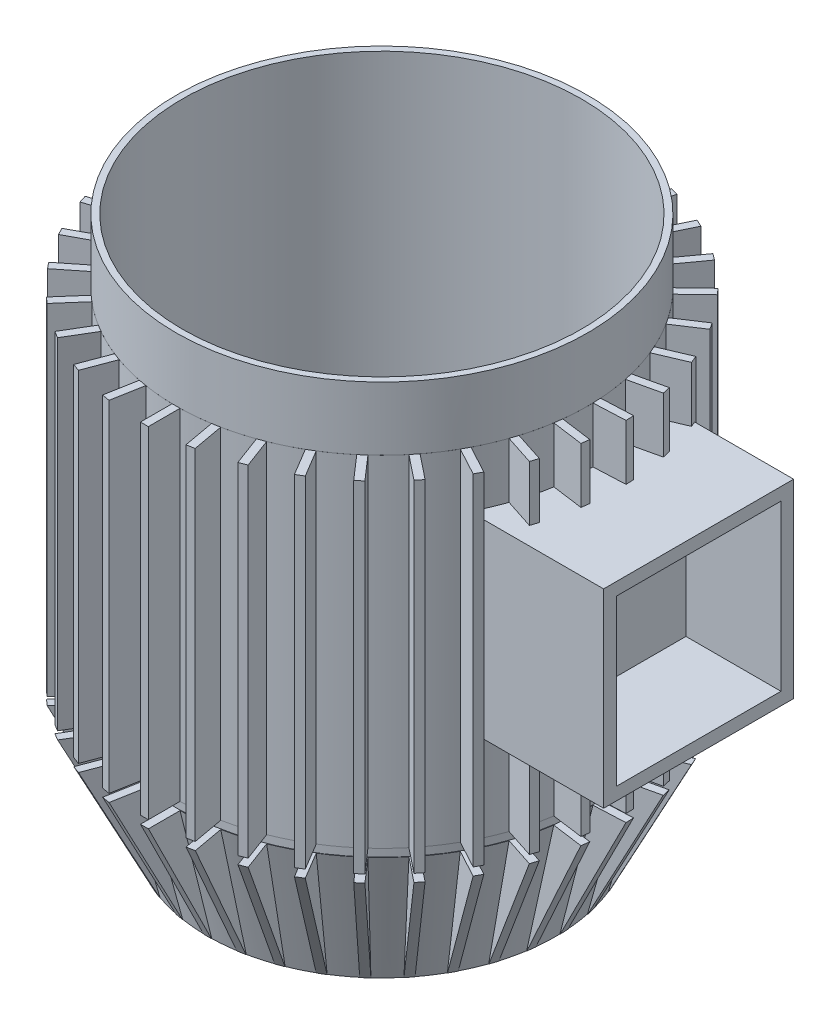
SolidWorks part; units mm, degrees
ref_plane "Front Plane" through (0, 0, 0) normal (0, 0, 1) x (1, 0, 0)
ref_plane "Top Plane" through (0, 0, 0) normal (0, 1, 0) x (1, 0, 0)
ref_plane "Right Plane" through (0, 0, 0) normal (1, 0, 0) x (0, 0, -1)
sketch "Sketch1" plane through (0, 0, 0) normal (0, 1, 0) x (1, 0, 0)
  circle A0 centre (0, 0) radius 1651
  dimension "D1" = 3302
extrude "Boss-Extrude1" add sketch "Sketch1" against normal blind 4318
chamfer "Chamfer1" distance 254 distance2 1016 1 edges at (0, -4318, 1651)
shell "Shell1" thickness 50.8
ref_plane "Plane4" through (0, 0, 1905) normal (0, 0, 1) x (1, 0, 0)
sketch "Sketch2" plane through (0, 0, 1905) normal (0, 0, 1) x (1, 0, 0)
  line L0 (1651, 0) -> (-1651, 0) construction
  line L1 (-31.75, 0) -> (31.75, 0)
  line L2 (-31.75, 0) -> (-31.75, -4318)
  line L3 (-31.75, -4318) -> (31.75, -4318)
  line L4 (31.75, 0) -> (31.75, -4318)
  line L5 (-1397, -4318) -> (1397, -4318) construction
  line L6 (0, 0) -> (0, -4565.7037) construction
  dimension "D1" = 63.5
extrude "Boss-Extrude2" add sketch "Sketch2" against normal up to next
pattern_circular "CirPattern1" count 35 over 360 about axis through (0, 0, 0) along (0, 1, 0) of "Boss-Extrude2"
sketch "Sketch3" plane through (0, 0, 0) normal (0, 0, 1) x (1, 0, 0)
  line L0 (-1398.8655, -4318) -> (-1904.5063, -3302)
  line L1 (-1904.5063, -4318) -> (-1904.5063, 0) construction
  line L2 (-1398.8655, -4318) -> (-2052.1864, -4573.4164)
  line L3 (-2052.1864, -4573.4164) -> (-2052.1864, -3238.5)
  line L4 (-2052.1864, -3238.5) -> (-1647.6081, -3238.5)
  line L7 (-1647.6081, -3302) -> (-1904.5063, -3302)
  line L8 (-1647.6081, -3238.5) -> (-1647.6081, -3302)
  line L9 (0, 0) -> (0, -4960.7075) construction
  dimension "D1" = 63.5
revolve "Cut-Revolve1" cut sketch "Sketch3" angle 360 about L9
sketch "Sketch4" plane through (0, -4318, 0) normal (0, -1, 0) x (1, 0, 0)
  circle A0 centre (0, 0) radius 254
  dimension "D1" = 508
extrude "Cut-Extrude1" cut sketch "Sketch4" against normal through all
ref_plane "Plane5" through (2540, 0, 0) normal (1, 0, 0) x (0, 0, -1)
sketch "Sketch6" plane through (2540, 0, 0) normal (1, 0, 0) x (0, 0, -1)
  line L0 (3763.1942, -2443.5551) -> (-1009.808, -1761.5916) construction
  line L1 (762, -2476.5) -> (-762, -2476.5)
  line L2 (762, -2476.5) -> (762, -952.5)
  line L3 (762, -952.5) -> (-762, -952.5)
  line L4 (-762, -2476.5) -> (-762, -952.5)
  line L5 (0, 0) -> (0, -4799.0579) construction
  line L7 (-1647.6081, -3238.5) -> (1647.6081, -3238.5) construction
  dimension "D1" = 1524
  dimension "D2" = 1524
  dimension "D3" = 762
extrude "Boss-Extrude3" add sketch "Sketch6" against normal up to next
sketch "Sketch7" plane through (2540, 0, 0) normal (1, 0, 0) x (0, 0, -1)
  line L0 (660.4, -1054.1) -> (-660.4, -1054.1)
  line L1 (-660.4, -1054.1) -> (-660.4, -2374.9)
  line L2 (-660.4, -2374.9) -> (660.4, -2374.9)
  line L3 (660.4, -2374.9) -> (660.4, -1054.1)
  line L4 (762, -2476.5) -> (762, -952.5)
  line L5 (762, -952.5) -> (-762, -952.5)
  line L6 (-762, -952.5) -> (-762, -2476.5)
  line L7 (-762, -2476.5) -> (762, -2476.5)
  line L8 (762, -2476.5) -> (762, -952.5)
  line L9 (762, -952.5) -> (-762, -952.5)
  line L10 (-762, -952.5) -> (-762, -2476.5)
  line L11 (-762, -2476.5) -> (762, -2476.5)
  dimension "D1" = 0
  dimension "D2" = 101.6
extrude "Cut-Extrude3" cut sketch "Sketch7" against normal blind 762 contours L0 L1 L2 L3
sketch "Sketch8" plane through (0, 0, 0) normal (1, 0, 0) x (0, 0, -1)
  line L0 (-1650.6947, -3238.5) -> (-1650.6947, 0) construction
  line L1 (-2144.3398, 0) -> (-1650.6947, 0)
  line L2 (-2144.3398, 0) -> (-2144.3398, -508)
  line L3 (-2144.3398, -508) -> (-1650.6947, -508)
  line L4 (-1650.6947, 0) -> (-1650.6947, -508)
  line L5 (-1650.6947, 0) -> (-1905, 0) construction
  line L6 (0, 0) -> (0, -4807.3928) construction
  line L7 (1600.2, 0) -> (-1600.2, 0) construction
  dimension "D1" = 508
revolve "Cut-Revolve2" cut sketch "Sketch8" angle 360 about L6
scale "Scale1" scale about centroid uniform scaling yes scale factor 0.02
